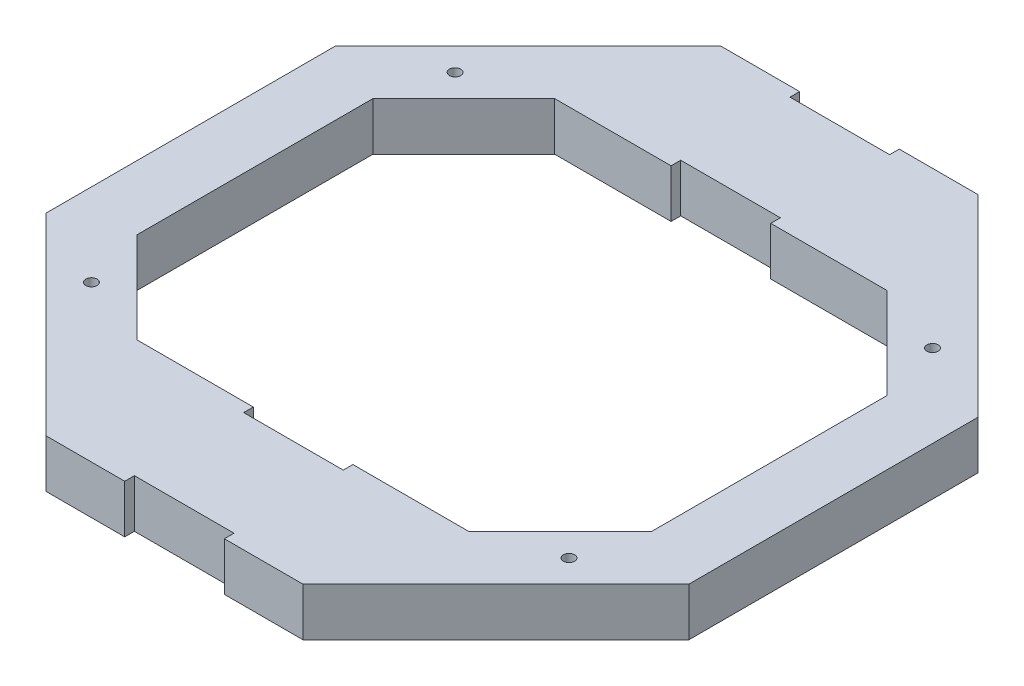
SolidWorks part; units mm, degrees
ref_plane "前视基准面" through (0, 0, 0) normal (0, 0, 1) x (1, 0, 0)
ref_plane "上视基准面" through (0, 0, 0) normal (0, 1, 0) x (1, 0, 0)
ref_plane "右视基准面" through (0, 0, 0) normal (1, 0, 0) x (0, 0, -1)
sketch "草图1" plane through (0, 0, 0) normal (0, 1, 0) x (1, 0, 0)
  line L0 (40, 105) -> (100, 45)
  line L1 (-40, 105) -> (-100, 45)
  line L2 (100, -45) -> (40, -105)
  line L3 (-100, -45) -> (-40, -105)
  line L4 (0, 105) -> (0, -105) construction
  line L5 (100, 0) -> (-100, 0) construction
  line L6 (-100, 45) -> (-100, -45)
  line L7 (-40, 105) -> (40, 105)
  line L8 (-80, -36.7157) -> (-80, 36.7157)
  line L9 (-80, 36.7157) -> (-51.7157, 65)
  line L10 (-51.7157, 65) -> (51.7157, 65)
  line L11 (-40, -105) -> (40, -105)
  line L12 (-51.7157, -65) -> (51.7157, -65)
  line L13 (-80, -36.7157) -> (-51.7157, -65)
  line L14 (100, 45) -> (100, -45)
  line L15 (80, 36.7157) -> (51.7157, 65)
  line L16 (80, -36.7157) -> (51.7157, -65)
  line L17 (80, -36.7157) -> (80, 36.7157)
  point P1 (0, 0)
  point P15 (-80, 0)
  point P17 (0, 65)
  point P19 (-100, 0)
  point P21 (0, 105)
  dimension "D1" = 90
  dimension "D2" = 80
  dimension "D3" = 40
  dimension "D4" = 20
  dimension "D5" = 210
  dimension "D6" = 20
extrude "15台" add sketch "草图1" along normal blind 15
sketch "草图2" plane through (0, 15, 0) normal (0, 1, 0) x (1, 0, 0)
  line L0 (0, 105) -> (0, 65) construction
  line L1 (40, 105) -> (-40, 105) construction
  line L2 (51.7157, 65) -> (-51.7157, 65) construction
  line L3 (0, 85) -> (35.1623, 85) construction
  line L4 (0, 0) -> (35.1623, 0) construction
  line L5 (-15.5, 105) -> (-15.5, 102)
  line L6 (-15.5, 65) -> (15.5, 65)
  line L7 (-15.5, 65) -> (-15.5, 68)
  line L8 (-15.5, 68) -> (15.5, 68)
  line L9 (15.5, 65) -> (15.5, 68)
  line L10 (15.5, 105) -> (15.5, 102)
  line L11 (-15.5, 102) -> (15.5, 102)
  line L12 (-15.5, 105) -> (15.5, 105)
  line L13 (15.5, -65) -> (15.5, -68)
  line L14 (-15.5, -68) -> (15.5, -68)
  line L15 (-15.5, -65) -> (-15.5, -68)
  line L16 (-15.5, -65) -> (15.5, -65)
  line L17 (-15.5, -105) -> (15.5, -105)
  line L18 (-15.5, -102) -> (15.5, -102)
  line L19 (15.5, -105) -> (15.5, -102)
  line L20 (-15.5, -105) -> (-15.5, -102)
  line L21 (-67.2183, -49.4975) -> (-81.3604, -63.6396) construction
  line L22 (-100, -45) -> (-40, -105) construction
  line L23 (-80, -36.7157) -> (-51.7157, -65) construction
  line L24 (-40, 105) -> (-100, 45) construction
  circle A0 centre (-74.2893, -56.5685) radius 1.75
  circle A1 centre (74.2893, 56.5685) radius 1.75
  circle A4 centre (-74.2893, 56.5685) radius 1.75
  circle A5 centre (74.2893, -56.5685) radius 1.75
  point P15 (0, 68)
  point P45 (0, 0)
  dimension "D3" = 3.5
  dimension "D1" = 31
  dimension "D2" = 3
  dimension "D5" = 90
  dimension "D4" = 2
extrude "切除-拉伸1" cut sketch "草图2" against normal through all both and the other way through all
sketch "草图3" plane through (0, 15, 0) normal (0, 1, 0) x (1, 0, 0)
  circle A4 centre (-74.2893, -56.5685) radius 4
  circle A8 centre (-74.2893, 56.5685) radius 4
  circle A9 centre (74.2893, -56.5685) radius 4
  circle A11 centre (74.2893, 56.5685) radius 4
  point P15 (0, 0)
  dimension "D1" = 8
